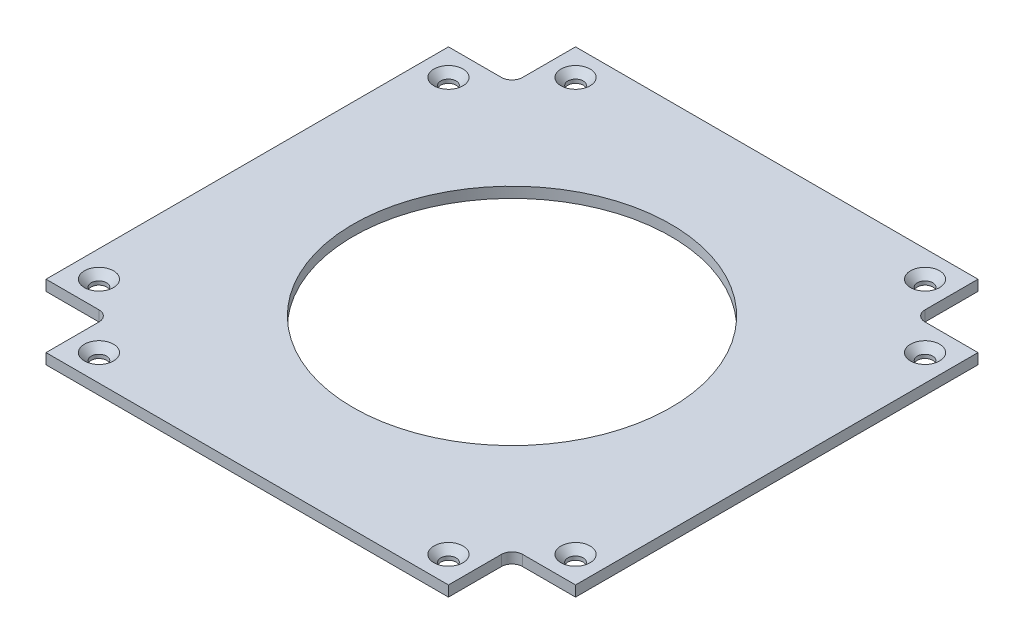
SolidWorks part; units mm, degrees
material "6061-T6 (SS)"
ref_plane "Piano frontale" through (0, 0, 0) normal (0, 0, 1) x (1, 0, 0)
ref_plane "Piano superiore" through (0, 0, 0) normal (0, 1, 0) x (1, 0, 0)
ref_plane "Piano destro" through (0, 0, 0) normal (1, 0, 0) x (0, 0, -1)
sketch "Schizzo1" plane through (0, 0, 0) normal (0, 1, 0) x (1, 0, 0)
  line L5 (0, -1000) -> (0, 49000) construction
  line L6 (-1000, 0) -> (49000, 0) construction
  line L8 (-50, -38) -> (-50, 38)
  line L9 (-50, 38) -> (-38, 38)
  line L10 (-38, 38) -> (-38, 50)
  line L11 (-38, 50) -> (38, 50)
  line L12 (38, 50) -> (38, 38)
  line L13 (38, 38) -> (50, 38)
  line L14 (50, 38) -> (50, -38)
  line L15 (50, -38) -> (38, -38)
  line L16 (38, -38) -> (38, -50)
  line L17 (38, -50) -> (-38, -50)
  line L18 (-38, -50) -> (-38, -38)
  line L19 (-38, -38) -> (-50, -38)
  circle A0 centre (0, 0) radius 30
  point P5 (0, 50)
  point P7 (-50, 0)
  dimension "D3" = 60
  dimension "D1" = 100
  dimension "D2" = 12
extrude "Estrusione-Estrusione1" add sketch "Schizzo1" along normal mid plane 2
fillet "Raccordo1" radius 2 4 edges at (-38, 0, -38) (38, 0, -38) (38, 0, 38) (-38, 0, 38)
hole_wizard "Foro svasato per Vite M2.5-1" positions "Schizzo3" profile "Schizzo4" countersink size "M2.5" standard "ISO" end condition through all
sketch "Schizzo3" plane through (0, 1, 0) normal (0, 1, 0) x (1, 0, 0)
  line L0 (-33, 45) -> (33, 45) construction
  line L1 (33, 45) -> (33, 33) construction
  line L2 (33, 33) -> (45, 33) construction
  line L3 (45, 33) -> (45, -33) construction
  line L4 (45, -33) -> (33, -33) construction
  line L5 (33, -33) -> (33, -45) construction
  line L6 (33, -45) -> (-33, -45) construction
  line L7 (-33, -45) -> (-33, -33) construction
  line L8 (-33, -33) -> (-45, -33) construction
  line L9 (-45, -33) -> (-45, 33) construction
  line L10 (-45, 33) -> (-33, 33) construction
  line L11 (-33, 33) -> (-33, 45) construction
  line L13 (-40, 38) -> (-50, 38) construction
  line L14 (-38, 50) -> (-38, 40) construction
  line L15 (50, 38) -> (40, 38) construction
  line L16 (-38, -40) -> (-38, -50) construction
  line L17 (-50, -38) -> (-40, -38) construction
  line L18 (38, 40) -> (38, 50) construction
  point P0 (-33, 45)
  point P2 (-45, 33)
  point P4 (-45, -33)
  point P6 (-33, -45)
  point P8 (33, -45)
  point P10 (45, -33)
  point P12 (45, 33)
  point P14 (33, 45)
  point P44 (-45, 38)
  point P45 (0, 0)
  point P49 (-38, 45)
  point P50 (0, 0)
  point P53 (45, 38)
  point P54 (0, 0)
  point P55 (-30.5656, -31.5667)
  point P56 (0, 0)
  point P57 (0, 0)
  point P62 (-38, -45)
  point P63 (-45, -34.1027)
  point P64 (0, 0)
  dimension "D1" = 5
  dimension "D2" = 5
  dimension "D3" = 5
  dimension "D4" = 5
sketch "Schizzo4" plane through (-33, 1, -45) normal (1, 0, 0) x (0, 0, 1)
  line L0 (0, 0) -> (0, 2)
  line L1 (0, 2) -> (1.45, 2)
  line L2 (1.45, 2) -> (1.45, 1.3)
  line L3 (1.45, 1.3) -> (2.75, 0)
  line L5 (2.75, 0) -> (0, 0)
  line L6 (-1.45, 1.3) -> (-2.75, 0) construction
  line L11 (0, -6.35) -> (0, 107.95) construction
  dimension "Thru Hole Dia." = 2.9
  dimension "Thru Hole Depth" = 2
  dimension "Near C'Sink Dia." = 5.5
  dimension "Near C'Sink Angle" = 90
